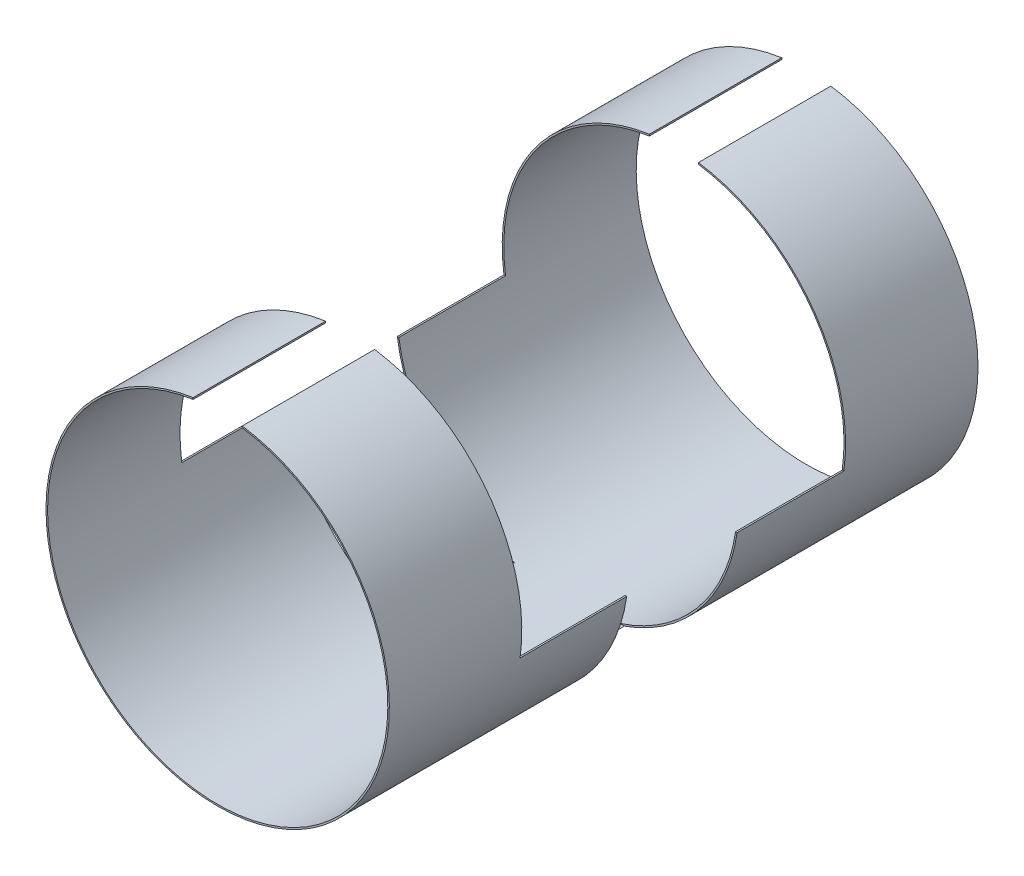
SolidWorks part; units mm, degrees
ref_plane "Front Plane" through (0, 0, 0) normal (0, 0, 1) x (1, 0, 0)
ref_plane "Top Plane" through (0, 0, 0) normal (0, 1, 0) x (1, 0, 0)
ref_plane "Right Plane" through (0, 0, 0) normal (1, 0, 0) x (0, 0, -1)
sketch "Sketch1" plane through (0, 0, 0) normal (0, 0, 1) x (1, 0, 0)
  circle A0 centre (0, 0) radius 44.45
  circle A1 centre (0, 0) radius 44.0436
  dimension "D1" = 88.9
  dimension "D2" = 0.4064
extrude "Extrude1" add sketch "Sketch1" along normal blind 152.4
sketch "Sketch2" plane through (0, 0, 152.4) normal (0, 0, 1) x (1, 0, 0)
  line L0 (0, 0) -> (0, 65.0049) construction
  line L1 (-6.35, 43.9941) -> (-6.35, 43.5834)
  line L2 (6.35, 43.9941) -> (6.35, 43.5834)
  circle A0 centre (0, 0) radius 44.45 construction
  circle A1 centre (0, 0) radius 44.0436 construction
  arc A3 (6.35, 43.9941) -> (-6.35, 43.9941) centre (0, 0) ccw
  arc A4 (6.35, 43.5834) -> (-6.35, 43.5834) centre (0, 0) ccw
  dimension "D1" = 6.35
  dimension "D2" = 6.35
extrude "Cut-Extrude1" cut sketch "Sketch2" against normal blind 152.4
sketch "Sketch3" plane through (0, 0, 0) normal (1, 0, 0) x (0, 0, -1)
  line L0 (-152.4, 43.9941) -> (-152.4, -44.45) construction
  line L1 (-118.11, 69.85) -> (-34.29, 69.85)
  line L2 (-118.11, 69.85) -> (-118.11, -6.35)
  line L3 (-118.11, -6.35) -> (-34.29, -6.35)
  line L4 (-34.29, 69.85) -> (-34.29, -6.35)
  line L5 (0, -44.45) -> (0, 43.9941) construction
  line L6 (-152.4, -44.45) -> (0, -44.45) construction
  dimension "D1" = 34.29
  dimension "D2" = 34.29
  dimension "D3" = 38.1
  dimension "D4" = 76.2
extrude "Cut-Extrude2" cut sketch "Sketch3" against normal blind 152.4 and the other way blind 152.4
sketch "Sketch4" plane through (0, 0, 0) normal (1, 0, 0) x (0, 0, -1)
  line L0 (-34.29, -6.35) -> (-118.11, -6.35) construction
  line L1 (-90.4875, -6.35) -> (-61.9125, -6.35)
  line L2 (-90.4875, -6.35) -> (-90.4875, -41.91)
  line L3 (-90.4875, -41.91) -> (-61.9125, -41.91)
  line L4 (-61.9125, -6.35) -> (-61.9125, -41.91)
  line L5 (-34.29, 43.9941) -> (-34.29, -6.35) construction
  line L7 (-118.11, -6.35) -> (-118.11, 43.9941) construction
  dimension "D1" = 28.575
  dimension "D2" = 41.91
  dimension "D3" = 27.6225
  dimension "D4" = 27.6225
extrude "Cut-Extrude3" cut sketch "Sketch4" against normal blind 152.4 and the other way blind 152.4
